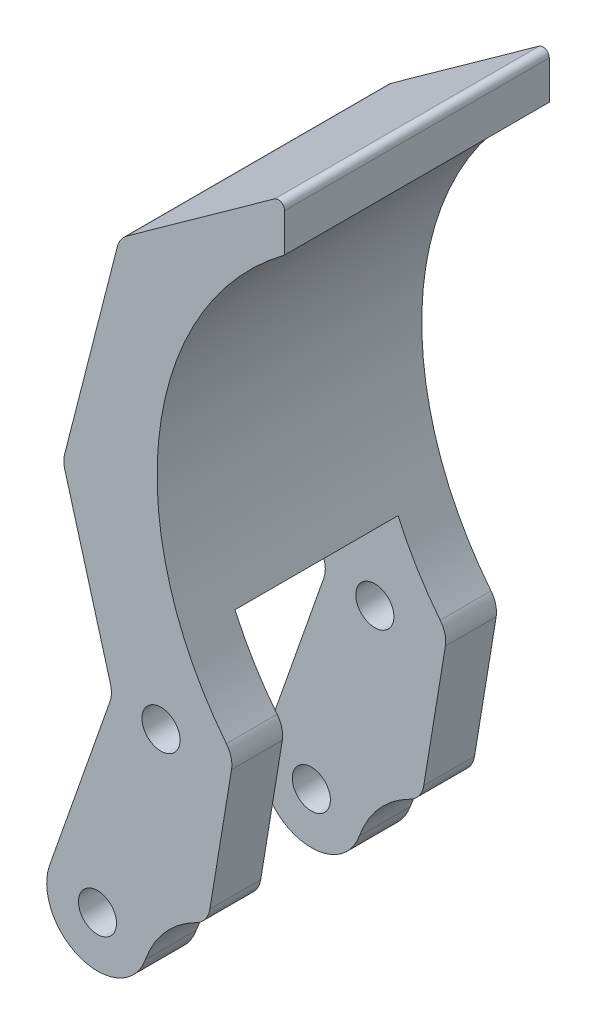
SolidWorks part; units mm, degrees
ref_plane "前视基准面" through (0, 0, 0) normal (0, 0, 1) x (1, 0, 0)
ref_plane "上视基准面" through (0, 0, 0) normal (0, 1, 0) x (1, 0, 0)
ref_plane "右视基准面" through (0, 0, 0) normal (1, 0, 0) x (0, 0, -1)
sketch "草图1" plane through (0, 0, 0) normal (0, 0, 1) x (1, 0, 0)
  line L1 (-44.759, 0) -> (37.6123, 0) construction
  line L2 (0, 0) -> (0, 68.6572) construction
  line L3 (23.6847, 21.3009) -> (7.0185, 2.6666) construction
  line L4 (29.6477, 15.9677) -> (12.9815, -2.6666) construction
  line L5 (30.4405, 19.9591) -> (22.8919, 17.3096) construction
  line L6 (16.1103, 33.6542) -> (17.8145, 23.2934) construction
  line L8 (30.4405, 19.9591) -> (25.6815, 33.5175) construction
  line L9 (25.6428, 34.7197) -> (29.2417, 47.5584) construction
  line L10 (29.2536, 48.5936) -> (25.1082, 64.8082) construction
  line L11 (19.8028, 35.3009) -> (3.1366, 16.6666) construction
  line L12 (23.5296, 31.9677) -> (6.8634, 13.3334) construction
  line L13 (24.3365, 65.9378) -> (12.7194, 74.273) construction
  line L14 (11.9279, 73.8667) -> (11.9279, 70.8409) construction
  line L15 (-23.6847, 21.3009) -> (-7.0185, 2.6666) construction
  line L16 (-29.6477, 15.9677) -> (-12.9815, -2.6666) construction
  line L17 (-23.5296, 31.9677) -> (-6.8634, 13.3334) construction
  line L18 (-19.8028, 35.3009) -> (-3.1366, 16.6666) construction
  line L19 (-16.1103, 33.6542) -> (-17.8145, 23.2934)
  line L20 (-30.4405, 19.9591) -> (-25.6815, 33.5175)
  line L25 (-25.6428, 34.7197) -> (-29.2417, 47.5584)
  line L26 (-5, 15) -> (-10, 0) construction
  line L27 (5, 15) -> (10, 0) construction
  line L28 (21.6662, 33.6343) -> (26.6662, 18.6343) construction
  line L29 (-29.2536, 48.5936) -> (-25.1082, 64.8082)
  line L30 (-24.3365, 65.9378) -> (-12.7194, 74.273)
  line L31 (-11.9279, 73.8667) -> (-11.9279, 70.8409)
  line L32 (-3.0291, 50.8087) -> (14.3488, 56.1034) construction
  circle A0 centre (-10, 0) radius 10 construction
  circle A4 centre (0, 51.7316) radius 15 construction
  circle A5 centre (10, 0) radius 4 construction
  circle A6 centre (10, 0) radius 10 construction
  arc A14 (22.8919, 17.3096) -> (17.993, 22.2086) centre (15.3434, 14.6601) ccw construction
  circle A16 centre (26.6662, 18.6343) radius 1.5 construction
  circle A17 centre (26.6662, 18.6343) radius 4 construction
  circle A18 centre (5, 15) radius 2.5 construction
  arc A19 (16.5198, 35.2255) -> (11.9279, 70.8409) centre (-3.0291, 50.8087) ccw construction
  circle A20 centre (21.6662, 33.6343) radius 2.5 construction
  circle A21 centre (-10, 0) radius 4 construction
  circle A22 centre (-26.6662, 18.6343) radius 1.5
  arc A23 (-30.4405, 19.9591) -> (-22.8919, 17.3096) centre (-26.6662, 18.6343) ccw
  arc A24 (-22.8919, 17.3096) -> (-18.8991, 21.8265) centre (-15.3434, 14.6601) cw
  circle A25 centre (-21.6662, 33.6343) radius 2.5 construction
  circle A26 centre (-5, 15) radius 2.5 construction
  circle A28 centre (-21.6662, 33.6343) radius 1.5
  circle A29 centre (-5, 15) radius 1.5 construction
  circle A30 centre (5, 15) radius 1.5 construction
  circle A31 centre (21.6662, 33.6343) radius 1.5 construction
  arc A33 (-18.8991, 21.8265) -> (-17.8145, 23.2934) centre (-19.788, 23.6181) ccw
  arc A40 (12.7194, 74.273) -> (11.9279, 73.8667) centre (12.4279, 73.8667) ccw construction
  arc A41 (18.8991, 21.8265) -> (17.8145, 23.2934) centre (19.788, 23.6181) cw construction
  arc A42 (16.1103, 33.6542) -> (16.5198, 35.2255) centre (18.0838, 33.9788) cw construction
  arc A43 (-16.5198, 35.2255) -> (-11.9279, 70.8409) centre (3.0291, 50.8087) cw
  arc A44 (25.6815, 33.5175) -> (25.6428, 34.7197) centre (27.5686, 34.1799) cw construction
  arc A45 (29.2417, 47.5584) -> (29.2536, 48.5936) centre (27.316, 48.0982) ccw construction
  arc A46 (25.1082, 64.8082) -> (24.3365, 65.9378) centre (23.1706, 64.3128) ccw construction
  arc A47 (-12.7194, 74.273) -> (-11.9279, 73.8667) centre (-12.4279, 73.8667) cw
  arc A48 (-16.1103, 33.6542) -> (-16.5198, 35.2255) centre (-18.0838, 33.9788) ccw
  arc A49 (-25.6815, 33.5175) -> (-25.6428, 34.7197) centre (-27.5686, 34.1799) ccw
  arc A50 (-29.2417, 47.5584) -> (-29.2536, 48.5936) centre (-27.316, 48.0982) cw
  arc A51 (-25.1082, 64.8082) -> (-24.3365, 65.9378) centre (-23.1706, 64.3128) cw
  point P93 (11.9279, 74.8409)
  point P96 (15.9627, 34.5512)
  point P99 (25.4726, 34.1125)
  point P102 (29.3864, 48.0744)
  point P105 (24.9279, 65.5135)
  point P109 (-11.9279, 74.8409)
  point P112 (-15.9627, 34.5512)
  point P115 (-25.4726, 34.1125)
  point P118 (-17.993, 22.2086)
  point P122 (-29.3864, 48.0744)
  point P125 (-24.9279, 65.5135)
  dimension "D1" = 30
  dimension "D3" = 20
  dimension "D4" = 25
  dimension "D5" = 8
  dimension "D6" = 3
  dimension "D7" = 2
  dimension "D8" = 8
  dimension "D13" = 25
  dimension "D20" = 140
  dimension "D21" = 5
  dimension "D27" = 3
  dimension "D29" = 0.5
  dimension "D28" = 16
  dimension "D30" = 2
  dimension "D14" = 4
  dimension "D12" = 10.5
  dimension "D18" = 150
  dimension "D10" = 0.5
  dimension "D26" = 2
  dimension "D9" = 11
  dimension "D11" = 15
  dimension "D15" = 10
  dimension "D16" = 145
  dimension "D17" = 14.5
  dimension "D19" = 18
  dimension "D22" = 5
  dimension "D23" = 15
  dimension "D24" = 25
  dimension "D25" = 3.75
extrude "凸台-拉伸1" add sketch "草图1" along normal blind 4
sketch "草图2" plane through (0, 0, 0) normal (0, 0, 1) x (1, 0, 0)
  line L0 (-26.7731, 38.7518) -> (-19.8346, 40.6968)
  line L1 (-29.2417, 47.5584) -> (-26.7731, 38.7518)
  line L6 (-11.9279, 70.8409) -> (-11.9279, 73.8667)
  line L7 (-12.7194, 74.273) -> (-24.3365, 65.9378)
  line L8 (-25.1082, 64.8082) -> (-29.2536, 48.5936)
  line L9 (-29.2417, 47.5584) -> (-25.6428, 34.7197)
  line L10 (-25.6815, 33.5175) -> (-30.4405, 19.9591)
  line L11 (-17.8145, 23.2934) -> (-16.1103, 33.6542)
  line L12 (-11.9279, 70.8409) -> (-11.9279, 73.8667)
  line L13 (-12.7194, 74.273) -> (-24.3365, 65.9378)
  line L14 (-25.1082, 64.8082) -> (-29.2536, 48.5936)
  arc A9 (-11.9279, 70.8409) -> (-16.5198, 35.2255) centre (3.0291, 50.8087) ccw
  arc A10 (-11.9279, 73.8667) -> (-12.7194, 74.273) centre (-12.4279, 73.8667) ccw
  arc A11 (-24.3365, 65.9378) -> (-25.1082, 64.8082) centre (-23.1706, 64.3128) ccw
  arc A12 (-29.2536, 48.5936) -> (-29.2417, 47.5584) centre (-27.316, 48.0982) ccw
  arc A13 (-25.6815, 33.5175) -> (-25.6428, 34.7197) centre (-27.5686, 34.1799) ccw
  arc A14 (-30.4405, 19.9591) -> (-22.8919, 17.3096) centre (-26.6662, 18.6343) ccw
  arc A15 (-18.8991, 21.8265) -> (-22.8919, 17.3096) centre (-15.3434, 14.6601) ccw
  arc A16 (-18.8991, 21.8265) -> (-17.8145, 23.2934) centre (-19.788, 23.6181) ccw
  arc A17 (-16.1103, 33.6542) -> (-16.5198, 35.2255) centre (-18.0838, 33.9788) ccw
  arc A18 (-11.9279, 70.8409) -> (-19.8346, 40.6968) centre (3.0291, 50.8087) ccw
  arc A19 (-11.9279, 73.8667) -> (-12.7194, 74.273) centre (-12.4279, 73.8667) ccw
  arc A20 (-24.3365, 65.9378) -> (-25.1082, 64.8082) centre (-23.1706, 64.3128) ccw
  arc A21 (-29.2536, 48.5936) -> (-29.2417, 47.5584) centre (-27.316, 48.0982) ccw
  point P10 (0, 0)
  dimension "D1" = 0
extrude "凸台-拉伸2" add sketch "草图2" along normal blind 20.84
ref_plane "基准面1" through (0, 0, 20.84) normal (0, 0, 1) x (1, 0, 0)
sketch "草图5" plane through (0, 0, 20.84) normal (0, 0, 1) x (1, 0, 0)
  line L4 (-19.8346, 40.6968) -> (-26.7731, 38.7518)
  line L5 (-26.7731, 38.7518) -> (-25.6428, 34.7197)
  line L6 (-25.6815, 33.5175) -> (-30.4405, 19.9591)
  line L7 (-17.8145, 23.2934) -> (-16.1103, 33.6542)
  line L8 (-19.8346, 40.6968) -> (-26.7731, 38.7518)
  line L9 (-26.7731, 38.7518) -> (-25.6428, 34.7197)
  line L10 (-25.6815, 33.5175) -> (-30.4405, 19.9591)
  line L11 (-17.8145, 23.2934) -> (-16.1103, 33.6542)
  arc A6 (-25.6815, 33.5175) -> (-25.6428, 34.7197) centre (-27.5686, 34.1799) ccw
  arc A7 (-30.4405, 19.9591) -> (-22.8919, 17.3096) centre (-26.6662, 18.6343) ccw
  arc A8 (-18.8991, 21.8265) -> (-22.8919, 17.3096) centre (-15.3434, 14.6601) ccw
  arc A9 (-18.8991, 21.8265) -> (-17.8145, 23.2934) centre (-19.788, 23.6181) ccw
  arc A10 (-16.1103, 33.6542) -> (-16.5198, 35.2255) centre (-18.0838, 33.9788) ccw
  arc A11 (-19.8346, 40.6968) -> (-16.5198, 35.2255) centre (3.0291, 50.8087) ccw
  arc A12 (-25.6815, 33.5175) -> (-25.6428, 34.7197) centre (-27.5686, 34.1799) ccw
  arc A13 (-30.4405, 19.9591) -> (-22.8919, 17.3096) centre (-26.6662, 18.6343) ccw
  arc A14 (-18.8991, 21.8265) -> (-22.8919, 17.3096) centre (-15.3434, 14.6601) ccw
  arc A15 (-18.8991, 21.8265) -> (-17.8145, 23.2934) centre (-19.788, 23.6181) ccw
  arc A16 (-16.1103, 33.6542) -> (-16.5198, 35.2255) centre (-18.0838, 33.9788) ccw
  arc A17 (-19.8346, 40.6968) -> (-16.5198, 35.2255) centre (3.0291, 50.8087) ccw
  dimension "D1" = 0
extrude "凸台-拉伸3" add sketch "草图5" against normal blind 4
ref_plane "基准面2" through (0, 0, 0) normal (0, 0, -1) x (-1, 0, 0)
sketch "草图8" plane through (0, 0, 0) normal (0, 0, -1) x (-1, 0, 0)
  circle A0 centre (21.6662, 33.6343) radius 1.5
  circle A1 centre (26.6662, 18.6343) radius 1.5
extrude "切除-拉伸1" cut sketch "草图8" against normal through all
